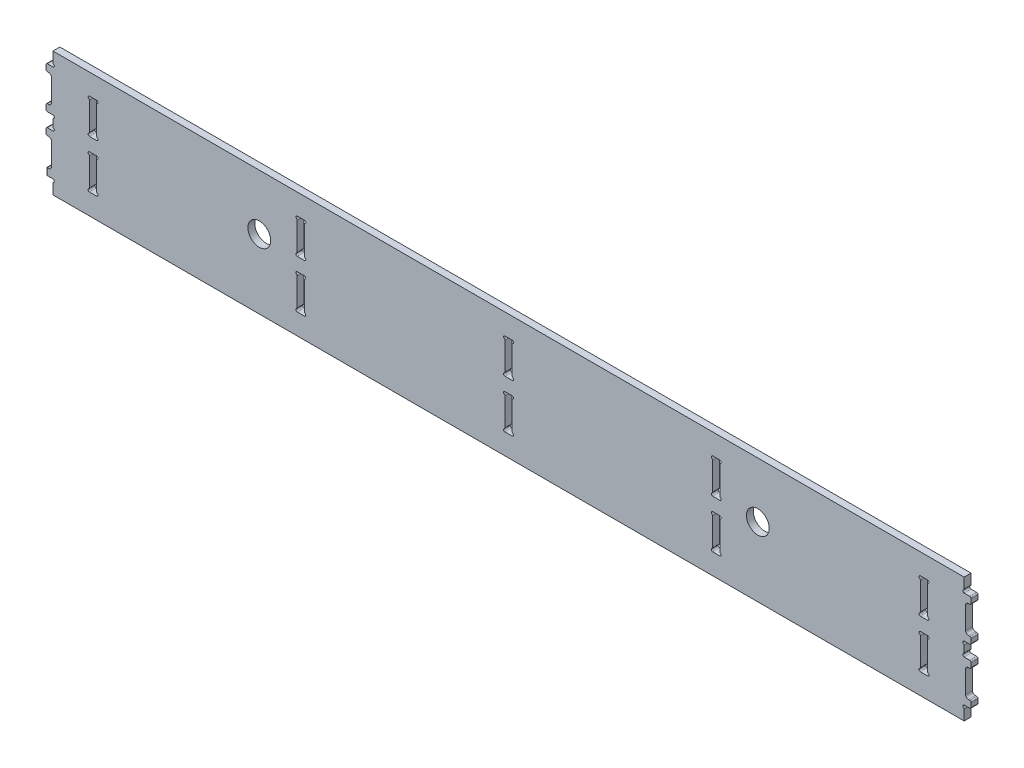
SolidWorks part; units mm, degrees
material "Plain Carbon Steel"
ref_plane "Front Plane" through (0, 0, 0) normal (0, 0, 1) x (1, 0, 0)
ref_plane "Top Plane" through (0, 0, 0) normal (0, 1, 0) x (1, 0, 0)
ref_plane "Right Plane" through (0, 0, 0) normal (1, 0, 0) x (0, 0, -1)
sketch "Sketch1" plane through (0, 0, 0) normal (0, 0, 1) x (1, 0, 0)
  line L0 (55, 0) -> (-55, 0) construction
  line L1 (-329, 0) -> (329, 0)
  line L2 (-329, 0) -> (-329, 90)
  line L3 (-329, 90) -> (329, 90)
  line L4 (329, 0) -> (329, 90)
  point P6 (0, 0)
  dimension "D1" = 658
  dimension "D2" = 90
extrude "Boss-Extrude1" add sketch "Sketch1" along normal blind 5
sketch "Sketch2" plane through (-329, 0, 0) normal (-1, 0, 0) x (0, 0, 1)
  line L0 (0, 90) -> (0, 0) construction
  line L1 (0, 80) -> (5, 80)
  line L2 (0, 80) -> (0, 50)
  line L3 (0, 50) -> (5, 50)
  line L4 (5, 80) -> (5, 50)
  line L5 (5, 90) -> (5, 0) construction
  line L6 (5, 90) -> (0, 90) construction
  line L7 (0, 40) -> (5, 40)
  line L8 (0, 40) -> (0, 10)
  line L9 (0, 10) -> (5, 10)
  line L10 (5, 40) -> (5, 10)
  line L12 (5, 0) -> (0, 0) construction
  point P14 (2.5, 80)
  point P15 (2.5, 50)
  dimension "D1" = 10
  dimension "D2" = 30
  dimension "D3" = 30
  dimension "D4" = 10
extrude "Boss-Extrude2" add sketch "Sketch2" along normal blind 5
sketch "Sketch3" plane through (-334, 0, 0) normal (-1, 0, 0) x (0, 0, 1)
  line L0 (0, 80) -> (0, 50) construction
  line L1 (0, 75) -> (5, 75)
  line L2 (0, 75) -> (0, 55)
  line L3 (0, 55) -> (5, 55)
  line L4 (5, 75) -> (5, 55)
  line L5 (5, 50) -> (5, 80) construction
  line L6 (0, 40) -> (0, 10) construction
  line L7 (0, 35) -> (5, 35)
  line L8 (0, 35) -> (0, 15)
  line L9 (0, 15) -> (5, 15)
  line L10 (5, 35) -> (5, 15)
  line L11 (5, 10) -> (5, 40) construction
  line L12 (5, 80) -> (0, 80) construction
  line L13 (0, 50) -> (5, 50) construction
  line L14 (5, 40) -> (0, 40) construction
  line L15 (0, 10) -> (5, 10) construction
  dimension "D1" = 5
  dimension "D2" = 5
  dimension "D3" = 5
  dimension "D4" = 5
extrude "Cut-Extrude1" cut sketch "Sketch3" against normal blind 4
mirror "Mirror1" about plane through (0, 0, 0) normal (1, 0, 0) of "Boss-Extrude2", "Cut-Extrude1"
fillet "Fillet1" radius 2 8 edges at (330, 55, 2.5) (330, 75, 2.5) (330, 35, 2.5) (330, 15, 2.5) (-330, 35, 2.5) (-330, 15, 2.5) (-330, 55, 2.5) (-330, 75, 2.5)
sketch "Sketch4" plane through (0, 0, 0) normal (0, 0, -1) x (-1, 0, 0)
  line L0 (-329, 80) -> (-329, 90) construction
  line L1 (-329, 40) -> (-329, 50) construction
  line L2 (-329, 0) -> (-329, 10) construction
  line L3 (0, 55) -> (0, -55) construction
  circle A0 centre (-329, 81) radius 1
  circle A1 centre (-329, 49) radius 1
  circle A2 centre (-329, 41) radius 1
  circle A3 centre (-329, 9) radius 1
  circle A4 centre (329, 9) radius 1
  circle A5 centre (329, 41) radius 1
  circle A6 centre (329, 49) radius 1
  circle A7 centre (329, 81) radius 1
  dimension "D1" = 2
extrude "Cut-Extrude2" cut sketch "Sketch4" against normal through all
fillet "Fillet2" radius 1 26 edges at (-334, 12.5, 5) (-334, 10, 2.5) (-334, 12.5, 0) (-334, 15, 2.5) (-329, 8, 2.5) (-334, 35, 2.5) (-334, 40, 2.5) (-329, 42, 2.5) (-329, 48, 2.5) (-334, 50, 2.5) (-334, 55, 2.5) (-334, 75, 2.5) (-334, 80, 2.5) (-329, 82, 2.5) (329, 8, 2.5) (334, 10, 2.5) (334, 15, 2.5) (334, 35, 2.5) (334, 40, 2.5) (329, 42, 2.5) (329, 48, 2.5) (334, 50, 2.5) (334, 55, 2.5) (334, 75, 2.5) (334, 80, 2.5) (329, 82, 2.5)
sketch "Sketch5" plane through (0, 0, 5) normal (0, 0, 1) x (1, 0, 0)
  line L0 (0, -2.75) -> (0, 2.75) construction
  line L1 (-2.6, 75) -> (2.6, 75)
  line L2 (-2.6, 75) -> (-2.6, 49.8)
  line L3 (-2.6, 49.8) -> (2.6, 49.8)
  line L4 (2.6, 75) -> (2.6, 49.8)
  line L5 (-2.6, 40.2) -> (2.6, 40.2)
  line L6 (-2.6, 40.2) -> (-2.6, 15)
  line L7 (-2.6, 15) -> (2.6, 15)
  line L8 (2.6, 40.2) -> (2.6, 15)
  line L9 (329, 90) -> (-329, 90) construction
  line L10 (-329, 0) -> (329, 0) construction
  line L11 (147.4, 75) -> (152.6, 75)
  line L12 (147.4, 75) -> (147.4, 49.8)
  line L13 (147.4, 49.8) -> (152.6, 49.8)
  line L14 (152.6, 75) -> (152.6, 49.8)
  line L15 (147.4, 40.2) -> (152.6, 40.2)
  line L16 (147.4, 40.2) -> (147.4, 15)
  line L17 (147.4, 15) -> (152.6, 15)
  line L18 (152.6, 40.2) -> (152.6, 15)
  line L19 (297.4, 75) -> (302.6, 75)
  line L20 (297.4, 75) -> (297.4, 49.8)
  line L21 (297.4, 49.8) -> (302.6, 49.8)
  line L22 (302.6, 75) -> (302.6, 49.8)
  line L23 (297.4, 40.2) -> (302.6, 40.2)
  line L24 (297.4, 40.2) -> (297.4, 15)
  line L25 (297.4, 15) -> (302.6, 15)
  line L26 (302.6, 40.2) -> (302.6, 15)
  line L27 (-302.6, 40.2) -> (-302.6, 15)
  line L28 (-297.4, 15) -> (-302.6, 15)
  line L29 (-297.4, 40.2) -> (-297.4, 15)
  line L30 (-297.4, 40.2) -> (-302.6, 40.2)
  line L31 (-302.6, 75) -> (-302.6, 49.8)
  line L32 (-297.4, 49.8) -> (-302.6, 49.8)
  line L33 (-297.4, 75) -> (-297.4, 49.8)
  line L34 (-297.4, 75) -> (-302.6, 75)
  line L35 (-152.6, 40.2) -> (-152.6, 15)
  line L36 (-147.4, 15) -> (-152.6, 15)
  line L37 (-147.4, 40.2) -> (-147.4, 15)
  line L38 (-147.4, 40.2) -> (-152.6, 40.2)
  line L39 (-152.6, 75) -> (-152.6, 49.8)
  line L40 (-147.4, 49.8) -> (-152.6, 49.8)
  line L41 (-147.4, 75) -> (-147.4, 49.8)
  line L42 (-147.4, 75) -> (-152.6, 75)
  point P8 (0, 75)
  dimension "D1" = 15
  dimension "D2" = 25.2
  dimension "D3" = 15
  dimension "D4" = 25.2
  dimension "D5" = 5.2
extrude "Cut-Extrude3" cut sketch "Sketch5" against normal through all
sketch "Sketch6" plane through (0, 0, 5) normal (0, 0, 1) x (1, 0, 0)
  line L0 (-302.6, 75) -> (-302.6, 49.8) construction
  line L1 (-297.4, 49.8) -> (-297.4, 75) construction
  line L2 (-302.6, 40.2) -> (-302.6, 15) construction
  line L3 (-297.4, 15) -> (-297.4, 40.2) construction
  line L4 (-297.4, 75) -> (-302.6, 75) construction
  circle A0 centre (-302.6, 74) radius 1
  circle A1 centre (-297.4, 74) radius 1
  circle A2 centre (-302.6, 50.8) radius 1
  circle A3 centre (-297.4, 50.8) radius 1
  circle A4 centre (-302.6, 39.2) radius 1
  circle A5 centre (-297.4, 39.2) radius 1
  circle A6 centre (-302.6, 16) radius 1
  circle A7 centre (-297.4, 16) radius 1
  circle A8 centre (-152.6, 74) radius 1
  circle A9 centre (-147.4, 74) radius 1
  circle A10 centre (-152.6, 50.8) radius 1
  circle A11 centre (-147.4, 50.8) radius 1
  circle A12 centre (-152.6, 39.2) radius 1
  circle A13 centre (-147.4, 39.2) radius 1
  circle A14 centre (-152.6, 16) radius 1
  circle A15 centre (-147.4, 16) radius 1
  circle A16 centre (-2.6, 74) radius 1
  circle A17 centre (2.6, 74) radius 1
  circle A18 centre (-2.6, 50.8) radius 1
  circle A19 centre (2.6, 50.8) radius 1
  circle A20 centre (-2.6, 39.2) radius 1
  circle A21 centre (2.6, 39.2) radius 1
  circle A22 centre (-2.6, 16) radius 1
  circle A23 centre (2.6, 16) radius 1
  circle A24 centre (147.4, 74) radius 1
  circle A25 centre (152.6, 74) radius 1
  circle A26 centre (147.4, 50.8) radius 1
  circle A27 centre (152.6, 50.8) radius 1
  circle A28 centre (147.4, 39.2) radius 1
  circle A29 centre (152.6, 39.2) radius 1
  circle A30 centre (147.4, 16) radius 1
  circle A31 centre (152.6, 16) radius 1
  circle A32 centre (297.4, 74) radius 1
  circle A33 centre (302.6, 74) radius 1
  circle A34 centre (297.4, 50.8) radius 1
  circle A35 centre (302.6, 50.8) radius 1
  circle A36 centre (297.4, 39.2) radius 1
  circle A37 centre (302.6, 39.2) radius 1
  circle A38 centre (297.4, 16) radius 1
  circle A39 centre (302.6, 16) radius 1
  dimension "D1" = 2
extrude "Cut-Extrude4" cut sketch "Sketch6" against normal through all
fillet "Fillet3" radius 1 40 edges at (297.4, 17, 2.5) (302.6, 17, 2.5) (302.6, 38.2, 2.5) (297.4, 38.2, 2.5) (297.4, 51.8, 2.5) (302.6, 51.8, 2.5) (302.6, 73, 2.5) (297.4, 73, 2.5) (147.4, 17, 2.5) (152.6, 17, 2.5) (152.6, 38.2, 2.5) (147.4, 38.2, 2.5) (147.4, 51.8, 2.5) (152.6, 51.8, 2.5) (152.6, 73, 2.5) (147.4, 73, 2.5) (-2.6, 17, 2.5) (2.6, 17, 2.5) (2.6, 38.2, 2.5) (-2.6, 38.2, 2.5) (-2.6, 51.8, 2.5) (2.6, 51.8, 2.5) (2.6, 73, 2.5) (-2.6, 73, 2.5) (-152.6, 17, 2.5) (-147.4, 17, 2.5) (-147.4, 51.8, 2.5) (-147.4, 38.2, 2.5) (-152.6, 38.2, 2.5) (-152.6, 51.8, 2.5) (-147.4, 73, 2.5) (-152.6, 73, 2.5) (-297.4, 17, 2.5) (-302.6, 17, 2.5) (-297.4, 38.2, 2.5) (-302.6, 38.2, 2.5) (-302.6, 51.8, 2.5) (-297.4, 51.8, 2.5) (-297.4, 73, 2.5) (-302.6, 73, 2.5)
ref_plane "Plane1" through (0, 0, 0) normal (0, 0, -1) x (-1, 0, 0)
extrude "Cut-Extrude5" cut sketch "Sketch7" along normal through all and the other way through all
sketch "Sketch7" plane through (-179.1148, -345.3303, 0) normal (0, 0, -1) x (-1, 0, 0)
  circle A2 centre (-359.1148, 395.3303) radius 8.25
  circle A3 centre (0.8852, 395.3303) radius 8.25
